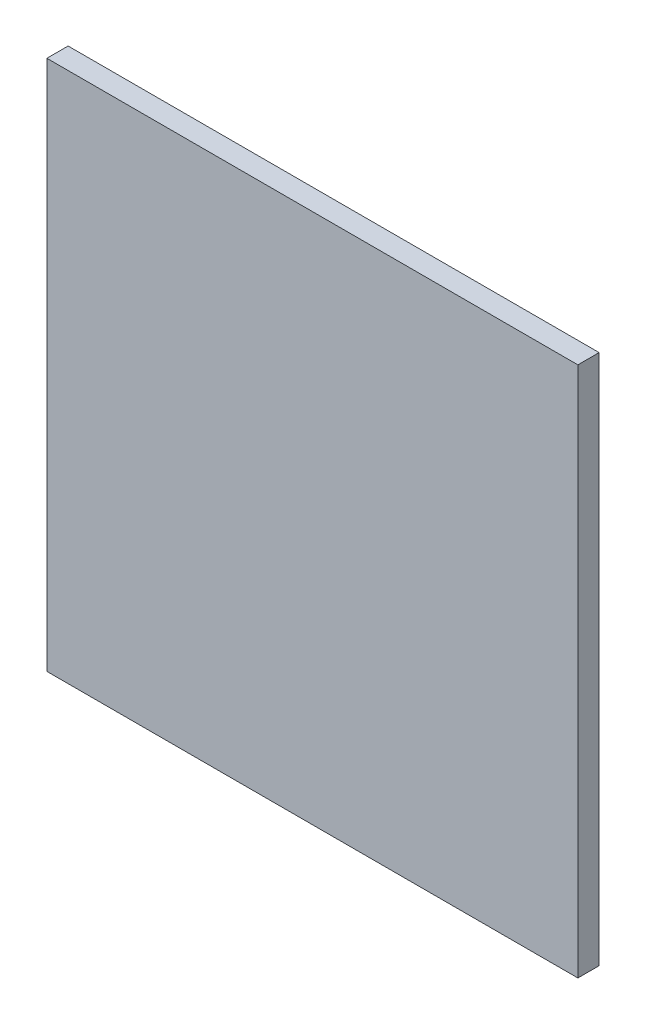
SolidWorks part; units mm, degrees
ref_plane "Front Plane" through (0, 0, 0) normal (0, 0, 1) x (1, 0, 0)
ref_plane "Top Plane" through (0, 0, 0) normal (0, 1, 0) x (1, 0, 0)
ref_plane "Right Plane" through (0, 0, 0) normal (1, 0, 0) x (0, 0, -1)
sketch "Sketch1" plane through (0, 0, 0) normal (0, 0, 1) x (1, 0, 0)
  line L1 (-15, -15) -> (15, -15)
  line L2 (-15, -15) -> (-15, 15)
  line L3 (-15, 15) -> (15, 15)
  line L4 (15, -15) -> (15, 15)
  line L5 (0, 15) -> (0, -15) construction
  line L6 (-15, 0) -> (15, 0) construction
  point P0 (0, 0)
  dimension "D1" = 30
  dimension "D2" = 30
extrude "Boss-Extrude1" add sketch "Sketch1" along normal blind 1.2
